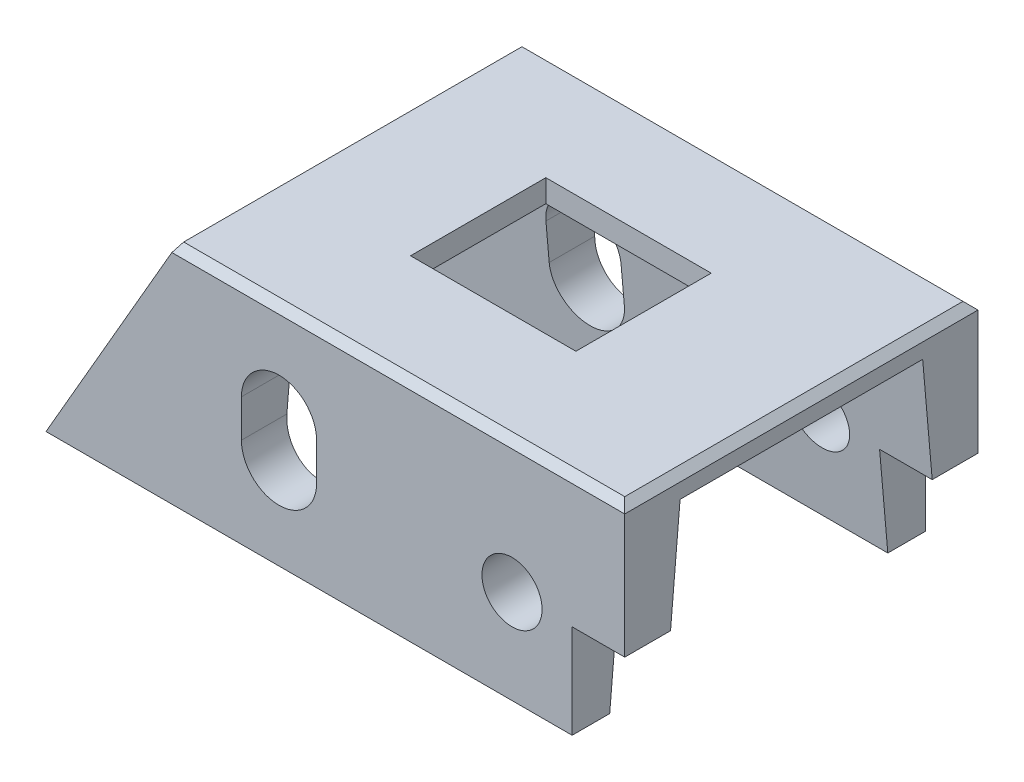
SolidWorks part; units mm, degrees
material "Alloy Steel"
ref_plane "Front Plane" through (0, 0, 0) normal (0, 0, 1) x (1, 0, 0)
ref_plane "Top Plane" through (0, 0, 0) normal (0, 1, 0) x (1, 0, 0)
ref_plane "Right Plane" through (0, 0, 0) normal (1, 0, 0) x (0, 0, -1)
sketch "Sketch1" plane through (0, 0, 0) normal (0, 0, 1) x (1, 0, 0)
  line L0 (-35, 0) -> (35, 0)
  line L1 (35, 0) -> (35, 12.5)
  line L2 (35, 12.5) -> (42, 12.5)
  line L3 (42, 12.5) -> (42, 30)
  line L4 (42, 30) -> (-17.6795, 30)
  line L5 (-17.6795, 30) -> (-35, 0)
  line L6 (-35, 0) -> (-35, 31.207) construction
  line L7 (-4, 12) -> (-4, 17) construction
  line L8 (-9, 12) -> (-9, 17)
  line L9 (1, 12) -> (1, 17)
  arc A0 (-9, 12) -> (1, 12) centre (-4, 12) ccw
  arc A1 (1, 17) -> (-9, 17) centre (-4, 17) ccw
  circle A2 centre (27, 12.5) radius 4
  point P4 (0, 0)
  point P12 (-4, 14.5)
  dimension "D10" = 8
  dimension "D1" = 77
  dimension "D2" = 30
  dimension "D3" = 30
  dimension "D4" = 12.5
  dimension "D5" = 7
  dimension "D6" = 10
  dimension "D7" = 5
  dimension "D8" = 31
  dimension "D9" = 12
  dimension "D11" = 15
extrude "Boss-Extrude1" add sketch "Sketch1" along normal mid plane 47
sketch "Sketch2" plane through (42, 0, 0) normal (1, 0, 0) x (0, 0, -1)
  line L0 (-18.5, 0) -> (18.5, 0)
  line L4 (-23.5, 0) -> (23.5, 0) construction
  line L6 (18.5, 0) -> (16.1378, 27)
  line L7 (-18.5, 0) -> (-16.1378, 27)
  line L8 (-16.1378, 27) -> (16.1378, 27)
  dimension "D2" = 85
  dimension "D3" = 85
extrude "Cut-Extrude1" cut sketch "Sketch2" against normal up to next
sketch "Sketch3" plane through (0, 30, 0) normal (0, 1, 0) x (1, 0, 0)
  line L0 (-35, -23.5) -> (-35, -18.5) construction
  line L1 (-1, -9) -> (21, -9)
  line L2 (-1, -9) -> (-1, 9)
  line L3 (-1, 9) -> (21, 9)
  line L4 (21, -9) -> (21, 9)
  line L5 (10, 9) -> (10, -9) construction
  line L6 (-1, 0) -> (21, 0) construction
  point P0 (10, 0)
  dimension "D1" = 22
  dimension "D2" = 18
  dimension "D3" = 34
extrude "Cut-Extrude2" cut sketch "Sketch3" against normal up to next
chamfer "Chamfer1" distance 1 angle 45 4 edges at (12.1603, 30, -23.5) (42, 30, 0) (12.1603, 30, 23.5) (-17.6795, 30, 0)
